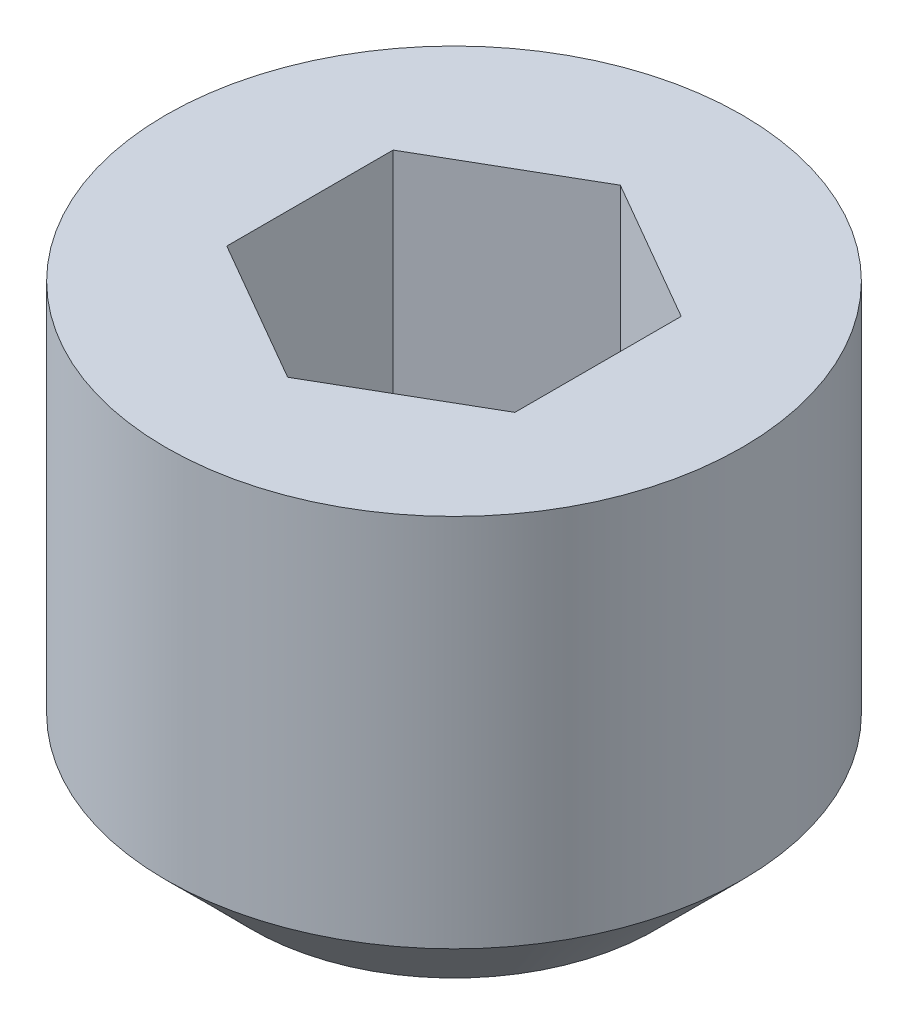
SolidWorks part; units mm, degrees
ref_plane "Front Plane" through (0, 0, 0) normal (0, 0, 1) x (1, 0, 0)
ref_plane "Top Plane" through (0, 0, 0) normal (0, 1, 0) x (1, 0, 0)
ref_plane "Right Plane" through (0, 0, 0) normal (1, 0, 0) x (0, 0, -1)
sketch "Sketch1" plane through (0, 0, 0) normal (0, 0, 1) x (1, 0, 0)
  line L0 (0, 4) -> (0, 0) construction
  line L2 (0, 4) -> (2.5, 4)
  line L3 (0, 4) -> (0, 0)
  line L4 (0, 0) -> (2.5, 0)
  line L5 (2.5, 4) -> (2.5, 0)
  dimension "SS_M" = 5
  dimension "SS_L" = 4
revolve "Revolve1" add sketch "Sketch1" angle 360 about L0
cosmetic thread "Cosmetic Thread1" parameters "SS_D1_s"=4.134
sketch "Sketch2" plane through (0, 0, 0) normal (0, 0, 1) x (1, 0, 0)
  line L0 (0, 4) -> (0, 1.2783) construction
  line L1 (0, 4) -> (1.25, 4)
  line L3 (1.25, 4) -> (1.25, 2)
  line L4 (1.25, 2) -> (0, 1.2783)
  line L5 (0, 1.2783) -> (0, 4)
  line L6 (2.5, 4) -> (-2.5, 4) construction
  dimension "D1" = 60
  dimension "SS_B" = 2.5
revolve "Cut-Revolve1" cut sketch "Sketch2" angle 360 about L0
sketch "Sketch3" plane through (0, 4, 0) normal (0, 1, 0) x (1, 0, 0)
  line L1 (0, 1.4434) -> (-1.25, 0.7217)
  line L2 (-1.25, 0.7217) -> (-1.25, -0.7217)
  line L3 (-1.25, -0.7217) -> (0, -1.4434)
  line L4 (0, -1.4434) -> (1.25, -0.7217)
  line L5 (1.25, -0.7217) -> (1.25, 0.7217)
  line L6 (1.25, 0.7217) -> (0, 1.4434)
  circle A0 centre (0, 0) radius 1.25 construction
  circle A1 centre (0, 0) radius 1.25 construction
extrude "Cut-Extrude1" cut sketch "Sketch3" against normal blind 2
sketch "Sketch4" plane through (0, 0, 0) normal (0, 0, 1) x (1, 0, 0)
  line L0 (0, 4) -> (0, 0) construction
  line L1 (2.5, 4) -> (2.5, 0) construction
  line L2 (-2.5, 0) -> (2.5, 0) construction
  line L3 (2.5, 0.75) -> (2.5, 0)
  line L4 (2.5, 0) -> (1.75, 0)
  line L5 (1.75, 0) -> (2.5, 0.75)
  dimension "D1" = 45
  dimension "SS_D_s" = 3.5
revolve "Cut-Revolve2" cut sketch "Sketch4" angle 360 about L0
